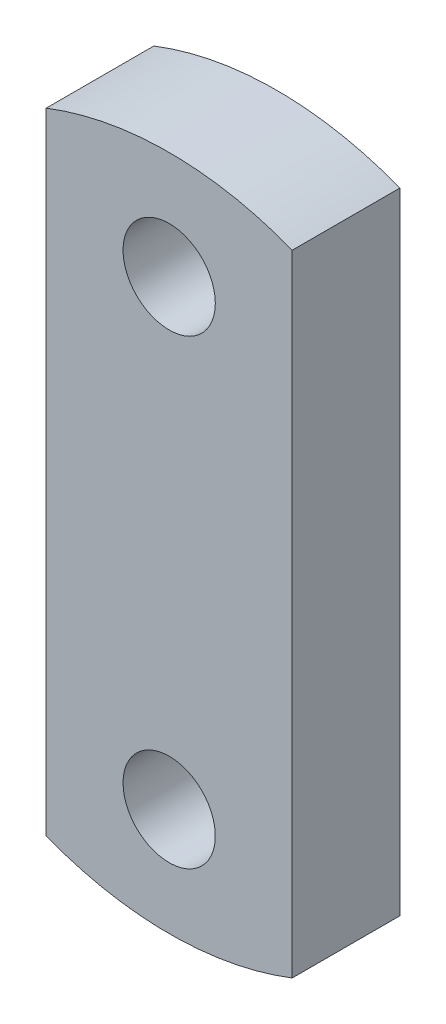
SolidWorks part; units mm, degrees
ref_plane "Front Plane" through (0, 0, 0) normal (0, 0, 1) x (1, 0, 0)
ref_plane "Top Plane" through (0, 0, 0) normal (0, 1, 0) x (1, 0, 0)
ref_plane "Right Plane" through (0, 0, 0) normal (1, 0, 0) x (0, 0, -1)
sketch "Sketch1" plane through (0, 0, 0) normal (0, 0, 1) x (1, 0, 0)
  line L0 (-40, 102.4695) -> (-40, -102.4695)
  line L2 (40, 102.4695) -> (40, -102.4695)
  line L3 (0, -55) -> (0, 55) construction
  line L4 (55, 0) -> (-55, 0) construction
  arc A0 (-40, -102.4695) -> (33.4783, -104.7817) centre (0, 0) ccw
  arc A1 (40, 102.4695) -> (-40, 102.4695) centre (0, 0) ccw
  circle A2 centre (0, 75) radius 15
  circle A3 centre (0, -75) radius 15
  arc A4 (33.4783, -104.7817) -> (40, -102.4695) centre (0, 0) ccw
  point P21 (30, -105.8301)
  dimension "D1" = 110
  dimension "D3" = 75
  dimension "D4" = 30
  dimension "D2" = 80
extrude "Boss-Extrude1" add sketch "Sketch1" along normal blind 35
